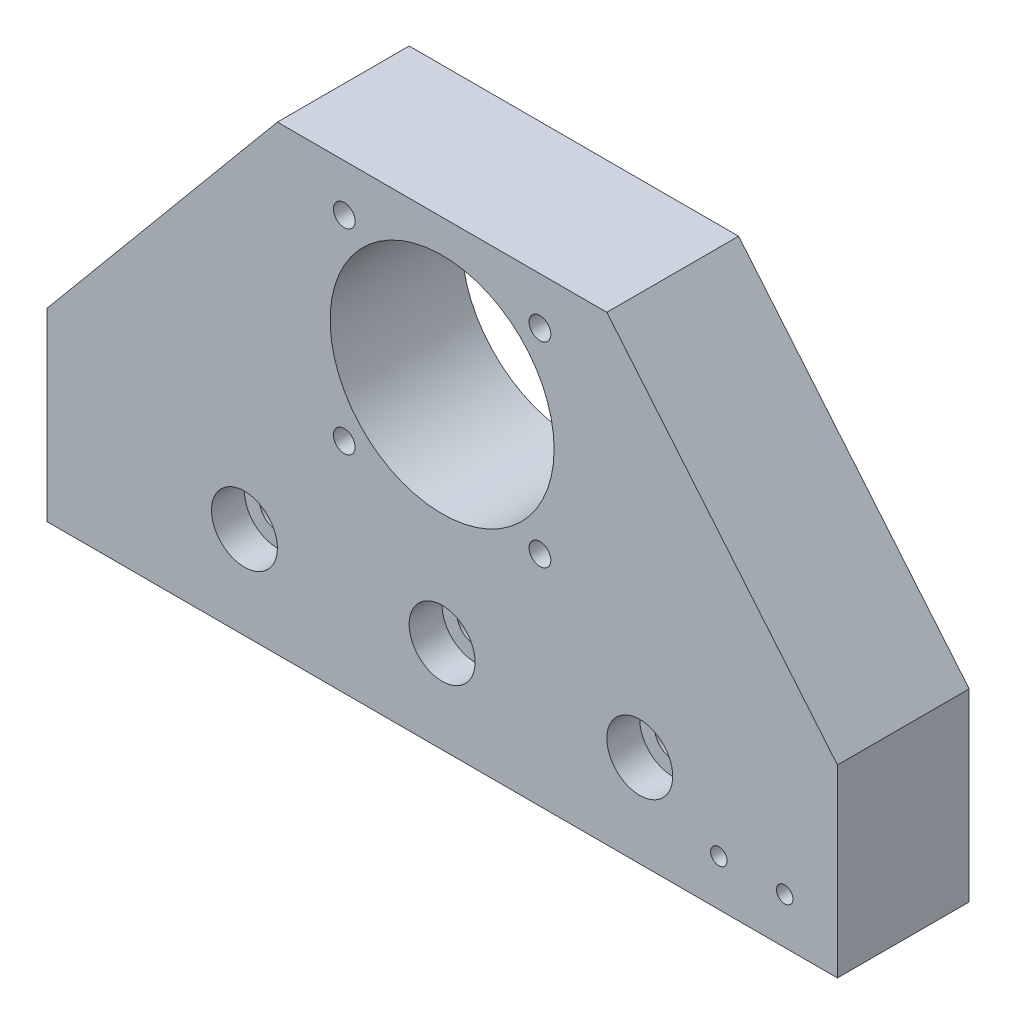
SolidWorks part; units mm, degrees
ref_plane "Front Plane" through (0, 0, 0) normal (0, 0, 1) x (1, 0, 0)
ref_plane "Top Plane" through (0, 0, 0) normal (0, 1, 0) x (1, 0, 0)
ref_plane "Right Plane" through (0, 0, 0) normal (1, 0, 0) x (0, 0, -1)
sketch "Sketch1" plane through (0, 0, 0) normal (0, 0, 1) x (1, 0, 0)
  line L0 (60, 0) -> (-60, 0)
  line L1 (-60, 0) -> (-60, 28)
  line L2 (-60, 28) -> (-25, 70)
  line L3 (-25, 70) -> (25, 70)
  line L4 (0, 0) -> (0, 70) construction
  line L5 (60, 28) -> (25, 70)
  line L6 (60, 0) -> (60, 28)
  dimension "D1" = 120
  dimension "D2" = 28
  dimension "D3" = 50
  dimension "D4" = 70
extrude "Boss-Extrude1" add sketch "Sketch1" along normal blind 20
sketch "Sketch2" plane through (0, 0, 20) normal (0, 0, 1) x (1, 0, 0)
  line L0 (0, 0) -> (0, 70) construction
  line L1 (-60, 0) -> (60, 0) construction
  line L2 (25, 70) -> (-25, 70) construction
  line L3 (-60, 14) -> (60, 14) construction
  line L4 (-60, 28) -> (-60, 0) construction
  line L5 (60, 0) -> (60, 28) construction
  point P12 (0, 14)
  point P13 (-30, 14)
  point P14 (30, 14)
  point P15 (0, 48)
  dimension "D1" = 30
hole_wizard "CBORE for M5 SHCS1" positions "3DSketch1" profile "Sketch3" counterbore size "M5" standard "ANSI Metric" end condition through all
sketch3d "3DSketch1"
  point P0 (-30, 14, 20)
  point P3 (0, 14, 20)
  point P6 (30, 14, 20)
sketch "Sketch3" plane through (-30, 14, 20) normal (1, 0, 0) x (0, -1, 0)
  line L0 (0, 0) -> (0, 20)
  line L1 (0, 20) -> (2.75, 20)
  line L3 (2.75, 20) -> (2.75, 5)
  line L4 (2.75, 5) -> (5, 5)
  line L5 (5, 5) -> (5, 0)
  line L7 (5, 0) -> (0, 0)
  line L11 (0, -6.35) -> (0, 107.95) construction
  dimension "Thru Hole Dia." = 5.5
  dimension "Thru Hole Depth" = 20
  dimension "C'Bore Dia." = 10
  dimension "C'Bore Depth" = 5
sketch "Sketch4" plane through (0, 0, 20) normal (0, 0, 1) x (1, 0, 0)
  circle A0 centre (0, 48) radius 17
  dimension "D1" = 34
extrude "Cut-Extrude1" cut sketch "Sketch4" against normal through all
sketch "Sketch5" plane through (0, 0, 20) normal (0, 0, 1) x (1, 0, 0)
  point P0 (14.8492, 33.1508)
  point P1 (-14.8492, 33.1508)
  point P2 (-14.8492, 62.8492)
  point P3 (14.8492, 62.8492)
hole_wizard "M4 Tapped Hole1" positions "3DSketch3" profile "Sketch7" tap size "M4" standard "ISO" end condition through all
sketch3d "3DSketch3"
  point P0 (-14.8492, 62.8492, 20)
  point P3 (14.8492, 62.8492, 20)
  point P6 (14.8492, 33.1508, 20)
  point P9 (-14.8492, 33.1508, 20)
sketch "Sketch7" plane through (-14.8492, 62.8492, 20) normal (1, 0, 0) x (0, -1, 0)
  line L0 (0, 0) -> (0, 20)
  line L1 (0, 20) -> (1.65, 20)
  line L2 (1.65, 20) -> (1.65, 0)
  line L5 (1.65, 0) -> (0, 0)
  line L11 (0, -6.35) -> (0, 107.95) construction
  dimension "Thread Major Dia." = 3.3
  dimension "Thru Tap Drill Depth" = 20
sketch "Sketch8" plane through (0, 0, 0) normal (0, -1, 0) x (1, 0, 0)
  line L0 (-20, 18.72) -> (-20, 0) construction
  line L1 (-60, 0) -> (60, 0) construction
  line L2 (20, 18.72) -> (20, 0) construction
  line L3 (-60, 10) -> (60, 10) construction
  line L4 (-60, 20) -> (-60, 0) construction
  line L5 (60, 20) -> (60, 0) construction
  line L6 (0, 0) -> (0, 20) construction
  point P12 (-20, 10)
  point P13 (20, 10)
  dimension "D1" = 20
  dimension "D2" = 20
hole_wizard "M4 Tapped Hole2" positions "Sketch10" profile "Sketch11" tap size "M4" standard "ISO"
sketch "Sketch10" plane through (0, 0, 0) normal (0, -1, 0) x (-1, 0, 0)
  point P0 (20, -10)
  point P3 (-20, -10)
sketch "Sketch11" plane through (-20, 0, 10) normal (1, 0, 0) x (0, 0, -1)
  line L0 (0, 0) -> (0, 15.9914)
  line L1 (0, 15.9914) -> (1.65, 15)
  line L2 (1.65, 15) -> (1.65, 0)
  line L5 (1.65, 0) -> (0, 0)
  line L10 (0, 15.9914) -> (-1.65, 15) construction
  line L11 (0, -6.35) -> (0, 107.95) construction
  dimension "Tap Drill Dia." = 3.3
  dimension "Tap Drill Depth" = 15
  dimension "Drill Angle" = 118
sketch "Sketch12" plane through (0, 0, 20) normal (0, 0, 1) x (1, 0, 0)
  line L0 (60, 0) -> (60, 28) construction
  line L2 (47, 0) -> (47, 14) construction
  line L3 (52, 7) -> (42, 7) construction
  line L5 (-60, 0) -> (60, 0) construction
  line L6 (-60, 14) -> (60, 14) construction
  point P9 (42, 7)
  point P10 (52, 7)
  dimension "D1" = 13
  dimension "D2" = 7
  dimension "D3" = 5
hole_wizard "M3 Tapped Hole1" positions "3DSketch5" profile "Sketch14" tap size "M3" standard "ISO"
sketch3d "3DSketch5"
  point P0 (42, 7, 20)
  point P3 (52, 7, 20)
sketch "Sketch14" plane through (42, 7, 20) normal (1, 0, 0) x (0, -1, 0)
  line L0 (0, 0) -> (0, 8.2511)
  line L1 (0, 8.2511) -> (1.25, 7.5)
  line L2 (1.25, 7.5) -> (1.25, 0)
  line L5 (1.25, 0) -> (0, 0)
  line L10 (0, 8.2511) -> (-1.25, 7.5) construction
  line L11 (0, -6.35) -> (0, 107.95) construction
  dimension "Tap Drill Dia." = 2.5
  dimension "Tap Drill Depth" = 7.5
  dimension "Drill Angle" = 118
